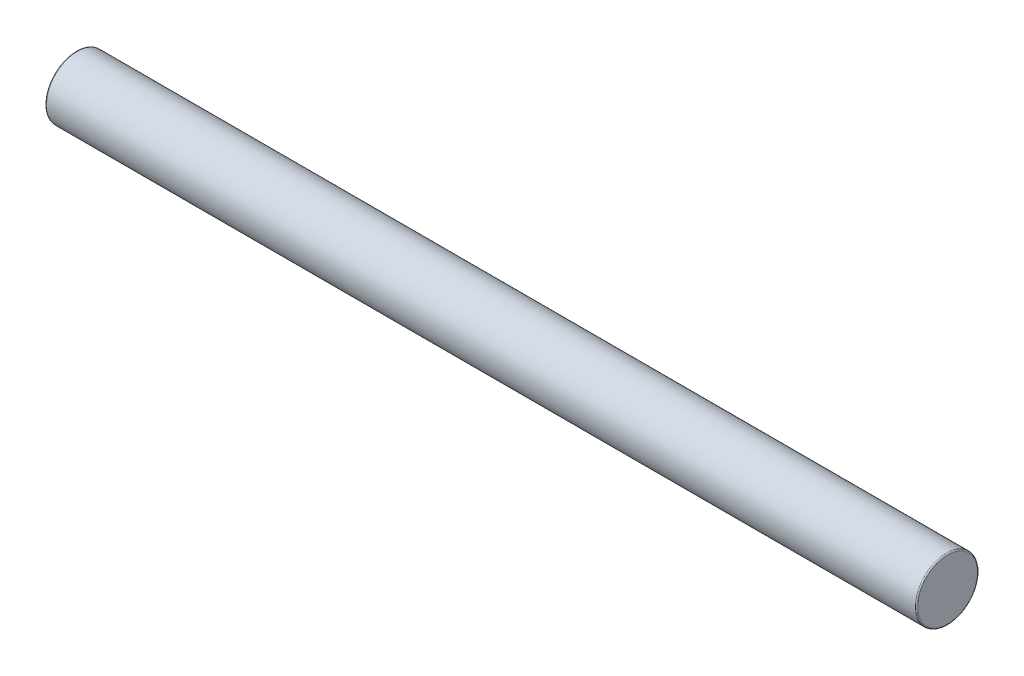
SolidWorks part; units mm, degrees
ref_plane "Front Plane" through (0, 0, 0) normal (0, 0, 1) x (1, 0, 0)
ref_plane "Top Plane" through (0, 0, 0) normal (0, 1, 0) x (1, 0, 0)
ref_plane "Right Plane" through (0, 0, 0) normal (1, 0, 0) x (0, 0, -1)
sketch "Sketch1" plane through (0, 0, 0) normal (1, 0, 0) x (0, 0, -1)
  circle A0 centre (0, 0) radius 5
  dimension "D1" = 10
extrude "Boss-Extrude1" add sketch "Sketch1" along normal blind 140
fillet "Fillet1" radius 0.2 2 edges at (140, 0, -5) (0, 0, -5)
